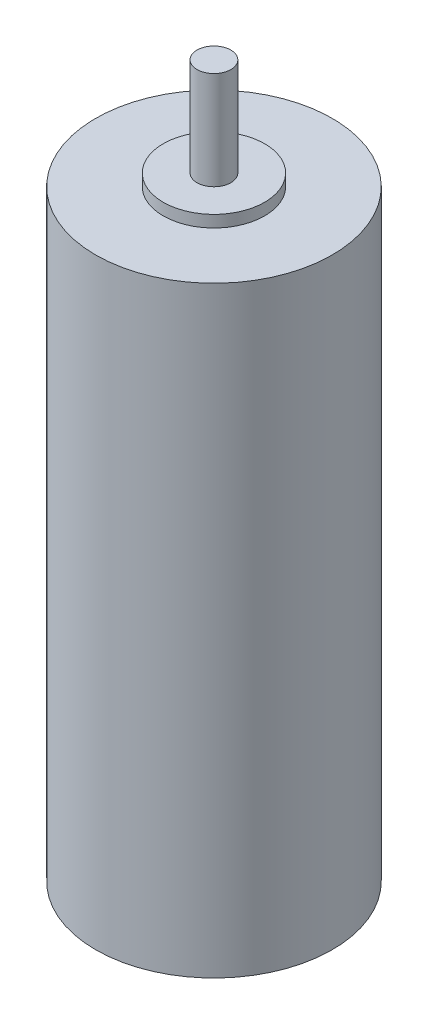
SolidWorks part; units mm, degrees
material "Vanadium"
ref_plane "Plan de face" through (0, 0, 0) normal (0, 0, 1) x (1, 0, 0)
ref_plane "Plan de dessus" through (0, 0, 0) normal (0, 1, 0) x (1, 0, 0)
ref_plane "Plan de droite" through (0, 0, 0) normal (1, 0, 0) x (0, 0, -1)
sketch "Sketch1" plane through (0, 0, 0) normal (0, 1, 0) x (1, 0, 0)
  circle A0 centre (0, 0) radius 7
  dimension "D1" = 14
extrude "Boss-Extrude1" add sketch "Sketch1" along normal blind 35.6
sketch "Sketch2" plane through (0, 35.6, 0) normal (0, 1, 0) x (1, 0, 0)
  circle A0 centre (0, 0) radius 3
  dimension "D1" = 6
extrude "Boss-Extrude2" add sketch "Sketch2" along normal blind 0.7
sketch "Sketch4" plane through (0, 35.6, 0) normal (0, 1, 0) x (1, 0, 0)
  circle A0 centre (0, 0) radius 1
  dimension "D1" = 2
extrude "Boss-Extrude3" add sketch "Sketch4" along normal blind 6.5
ref_point "Point1"
